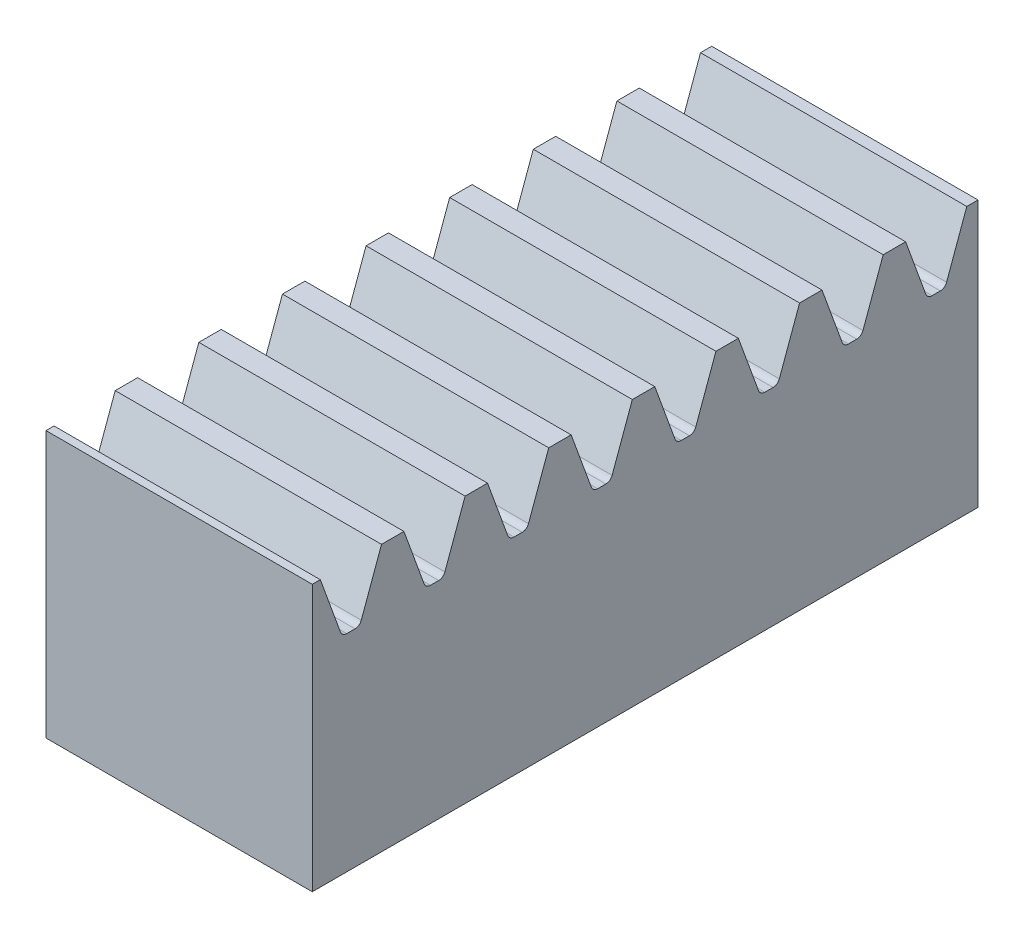
SolidWorks part; units mm, degrees
material "普通碳钢"
ref_plane "前视基准面" through (0, 0, 0) normal (0, 0, 1) x (1, 0, 0)
ref_plane "上视基准面" through (0, 0, 0) normal (0, 1, 0) x (1, 0, 0)
ref_plane "右视基准面" through (0, 0, 0) normal (1, 0, 0) x (0, 0, -1)
sketch "草图1" plane through (0, 0, 0) normal (0, 0, 1) x (1, 0, 0)
  line L0 (0, 0) -> (50000, 0) construction
  line L1 (0, 0) -> (0, 50000) construction
  line L3 (-10, 2) -> (10, 2)
  line L4 (-10, 2) -> (-10, -18)
  line L5 (-10, -18) -> (10, -18)
  line L6 (10, 2) -> (10, -18)
  line L7 (-10, 2) -> (10, -18) construction
  line L8 (-10, -18) -> (10, 2) construction
  point P5 (0, -8)
  dimension "D1" = 20
  dimension "D2" = 20
  dimension "D3" = 2
extrude "凸台-拉伸1" add sketch "草图1" along normal blind 50
sketch "草图2" plane through (-10, 0, 0) normal (-1, 0, 0) x (0, 0, 1)
  line L0 (3.14, -3.2036) -> (3.14, 49996.7964) construction
  line L1 (0, 0) -> (50000, 0) construction
  line L2 (0.8421, 2) -> (2.3602, -2.171)
  line L3 (50, 2) -> (0, 2) construction
  line L4 (2.83, -2.5) -> (3.45, -2.5)
  line L5 (3.9198, -2.171) -> (5.4379, 2)
  line L6 (5.4379, 2) -> (0.8421, 2)
  line L7 (0, 2) -> (0, -18) construction
  arc A0 (3.9198, -2.171) -> (3.45, -2.5) centre (3.45, -2) cw
  arc A1 (2.83, -2.5) -> (2.3602, -2.171) centre (2.83, -2) cw
  point P13 (1.57, 0)
  dimension "D5" = 40
  dimension "D4" = 0.5
  dimension "D1" = 3.14
  dimension "D2" = 1.57
  dimension "D3" = 2.5
extrude "切除-拉伸1" cut sketch "草图2" against normal through all
pattern_linear "阵列(线性)1" count 8 spacing 6.28 along (0, 0, 1) of "切除-拉伸1"
equation "\"M\"=2"
equation "\"a\"=20"
equation "\"ha\"=1"
equation "\"c\"=0.25"
equation "\"x\"=0"
equation "\"D3@草图1\"= \"M\" * ( \"ha\" + \"x\" )"
equation "\"D1@草图2\" = \"M\" * 3.14 * 0.5"
equation "\"D2@草图2\" = \"D1@草图2\" * 0.5"
equation "\"D3@草图2\"= \"M\" * ( \"ha\" + \"c\" - \"x\" )"
equation "\"D4@草图2\"= \"M\" * 0.25"
equation "\"D5@草图2\" = \"a\" * 2"
equation "\"D1@阵列(线性)1\"= \"D1@凸台-拉伸1\" / \"D3@阵列(线性)1\""
equation "\"D3@阵列(线性)1\"= \"D1@草图2\" * 2"
